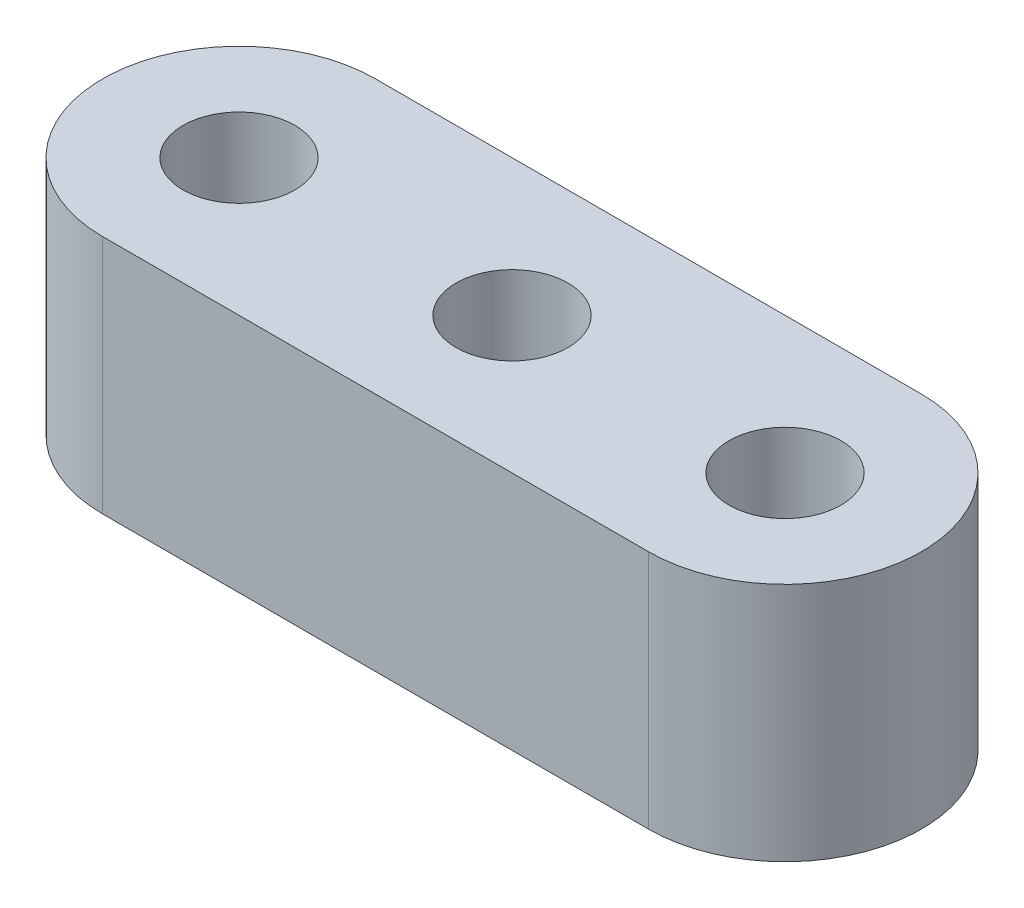
SolidWorks part; units mm, degrees
ref_plane "Front Plane" through (0, 0, 0) normal (0, 0, 1) x (1, 0, 0)
ref_plane "Top Plane" through (0, 0, 0) normal (0, 1, 0) x (1, 0, 0)
ref_plane "Right Plane" through (0, 0, 0) normal (1, 0, 0) x (0, 0, -1)
sketch "Sketch1" plane through (0, 0, 0) normal (0, 1, 0) x (1, 0, 0)
  line L0 (-10, -5) -> (-7.95, -5) construction
  line L1 (-10, 0) -> (-5, 0)
  line L2 (-10, -10) -> (-5, -10)
  line L3 (0, -33) -> (0, 33) construction
  line L4 (-5, 0) -> (5, 0)
  line L9 (5, 0) -> (10, 0)
  line L10 (0, 22.95) -> (0, 25) construction
  line L11 (-2.05, -5) -> (2.05, -5) construction
  line L12 (7.95, -5) -> (10, -5) construction
  line L14 (5, -10) -> (10, -10)
  line L15 (0, -7.05) -> (0, -2.95) construction
  line L16 (-5, -10) -> (5, -10)
  arc A0 (-10, 0) -> (-10, -10) centre (-10, -5) ccw
  arc A1 (10, -10) -> (10, 0) centre (10, -5) ccw
  circle A2 centre (10, -5) radius 2.05
  circle A3 centre (-10, -5) radius 2.05
  circle A4 centre (0, -5) radius 2.05
  point P2 (0, 0)
  point P17 (0, 0)
  point P18 (0, -5)
  dimension "D3" = 4.1
  dimension "D4" = 4.1
  dimension "D10" = 10
  dimension "D6" = 5
  dimension "D11" = 10
  dimension "D1" = 10
  dimension "D2" = 20
extrude "Boss-Extrude1" add sketch "Sketch1" along normal mid plane 8.8
sketch "Sketch2" plane through (0, 4.4, 0) normal (0, 1, 0) x (1, 0, 0)
  circle A0 centre (10, -5) radius 5
  circle A1 centre (10, -5) radius 2.05
